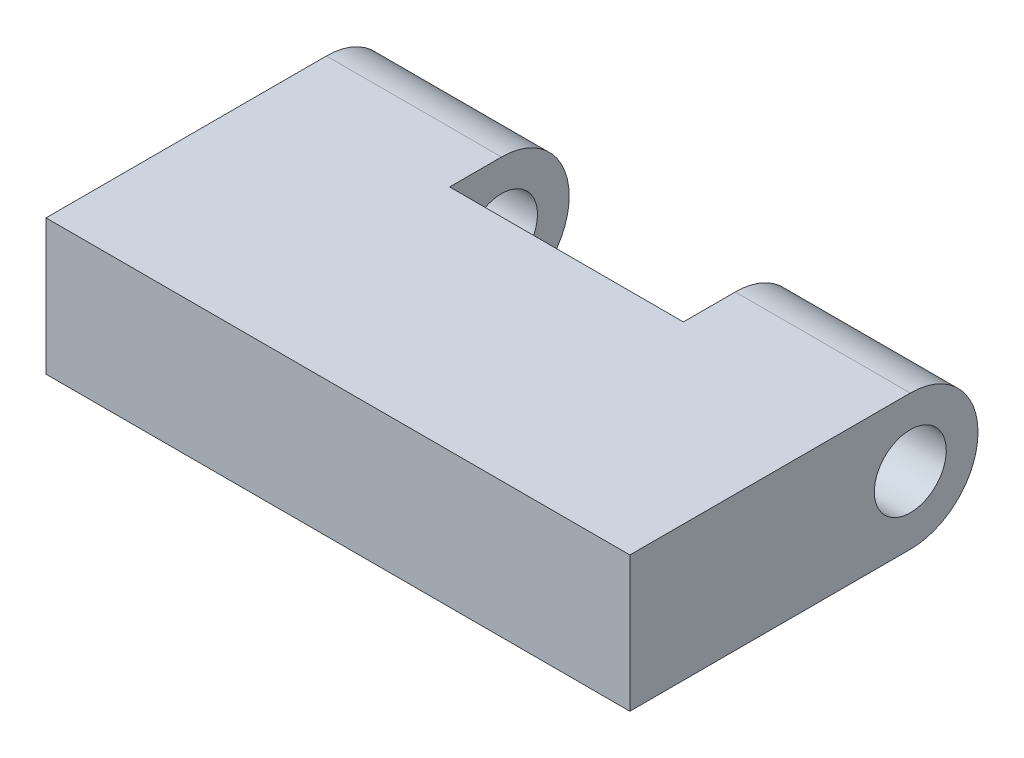
SolidWorks part; units mm, degrees
ref_plane "Front Plane" through (0, 0, 0) normal (0, 0, 1) x (1, 0, 0)
ref_plane "Top Plane" through (0, 0, 0) normal (0, 1, 0) x (1, 0, 0)
ref_plane "Right Plane" through (0, 0, 0) normal (1, 0, 0) x (0, 0, -1)
sketch "Sketch2" plane through (6.6781, 0, 0) normal (1, 0, 0) x (0, 0, -1)
  line L0 (2.0692, 21.4442) -> (-3.3687, 21.4442)
  line L2 (-3.3687, 13.7098) -> (2.0692, 13.7098)
  line L4 (-3.3687, 21.4442) -> (-13.9538, 21.4442)
  line L6 (-3.3687, 13.7098) -> (-13.9538, 13.7098)
  line L7 (-13.9538, 21.4442) -> (-13.9538, 13.7098)
  arc A0 (2.0692, 13.7098) -> (2.0692, 21.4442) centre (2.0692, 17.577) ccw
  circle A1 centre (2.0692, 17.577) radius 2.0555
extrude "Boss-Extrude1" add sketch "Sketch2" along normal blind 10
ref_plane "Plane1" through (0, 0, 0) normal (1, 0, 0) x (0, 0, -1)
mirror "Mirror2" about plane through (0, 0, 0) normal (1, 0, 0) of bodies 101
sketch "Sketch3" plane through (6.6781, 0, 0) normal (-1, 0, 0) x (0, 0, 1)
  line L0 (-2.0692, 21.4442) -> (13.9538, 21.4442) construction
  line L1 (13.9538, 13.7098) -> (0.8949, 13.7098)
  line L2 (13.9538, 13.7098) -> (13.9538, 21.4442)
  line L3 (13.9538, 21.4442) -> (0.8949, 21.4442)
  line L4 (0.8949, 13.7098) -> (0.8949, 21.4442)
extrude "Boss-Extrude2" add sketch "Sketch3" along normal up to surface (13.3562 mm away) up to face at (-6.6781, 17.577, 4.9755)
